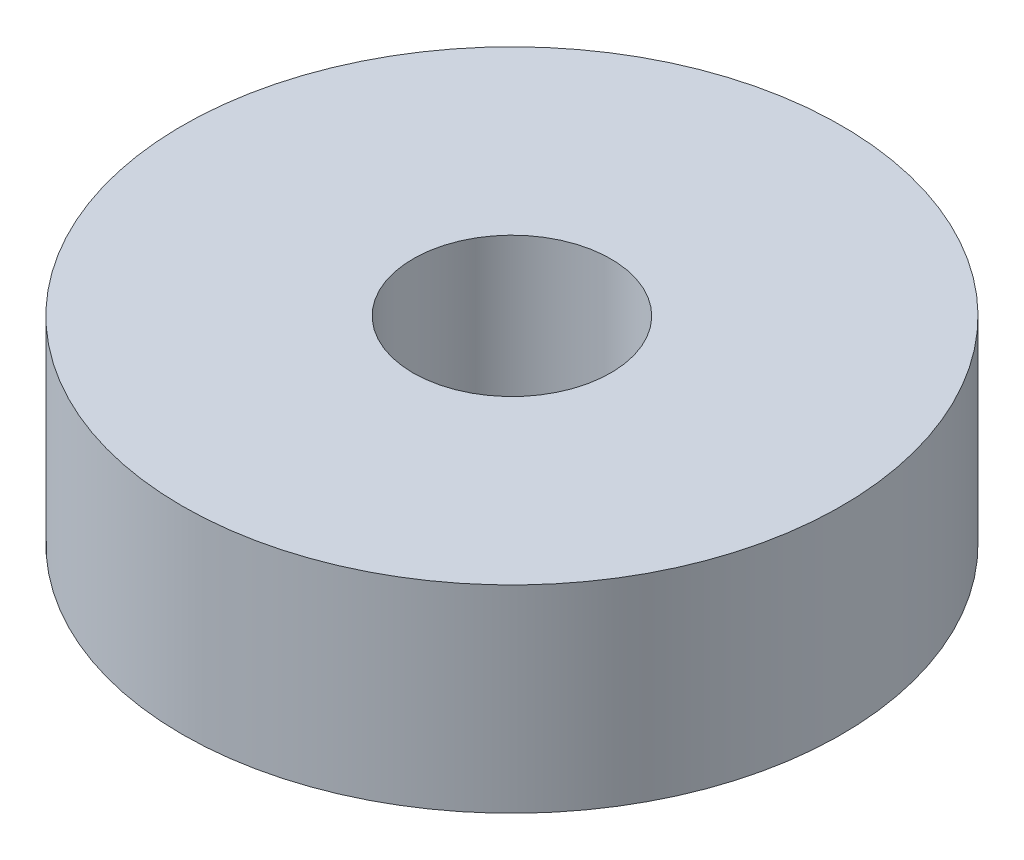
SolidWorks part; units mm, degrees
ref_plane "前视基准面" through (0, 0, 0) normal (0, 0, 1) x (1, 0, 0)
ref_plane "上视基准面" through (0, 0, 0) normal (0, 1, 0) x (1, 0, 0)
ref_plane "右视基准面" through (0, 0, 0) normal (1, 0, 0) x (0, 0, -1)
sketch "草图1" plane through (0, 0, 0) normal (0, 1, 0) x (1, 0, 0)
  circle A0 centre (0, 0) radius 10
  circle A1 centre (0, 0) radius 3
  dimension "D1" = 6
  dimension "D2" = 20
extrude "凸台-拉伸1" add sketch "草图1" along normal blind 6
